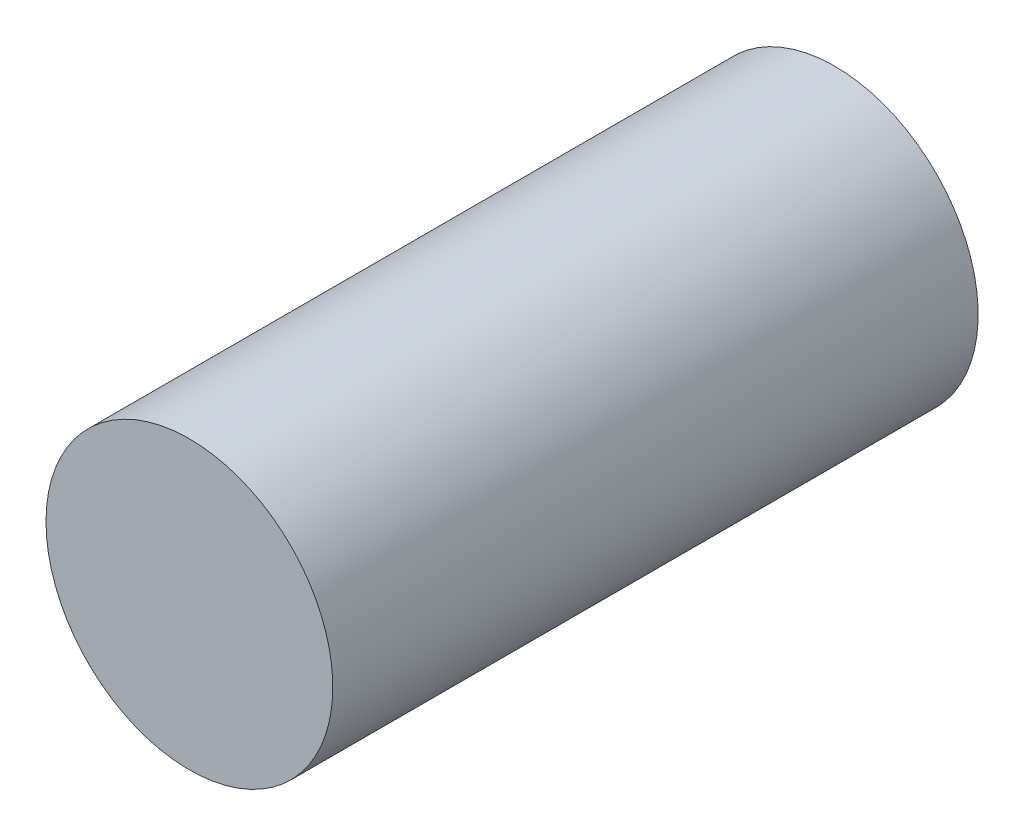
SolidWorks part; units mm, degrees
material "AISI 1020"
ref_plane "Front Plane" through (0, 0, 0) normal (0, 0, 1) x (1, 0, 0)
ref_plane "Top Plane" through (0, 0, 0) normal (0, 1, 0) x (1, 0, 0)
ref_plane "Right Plane" through (0, 0, 0) normal (1, 0, 0) x (0, 0, -1)
sketch "Sketch1" plane through (0, 0, 0) normal (0, 0, 1) x (1, 0, 0)
  circle A0 centre (0, 0) radius 5
  dimension "D1" = 10
extrude "Boss-Extrude1" add sketch "Sketch1" along normal blind 22.5
